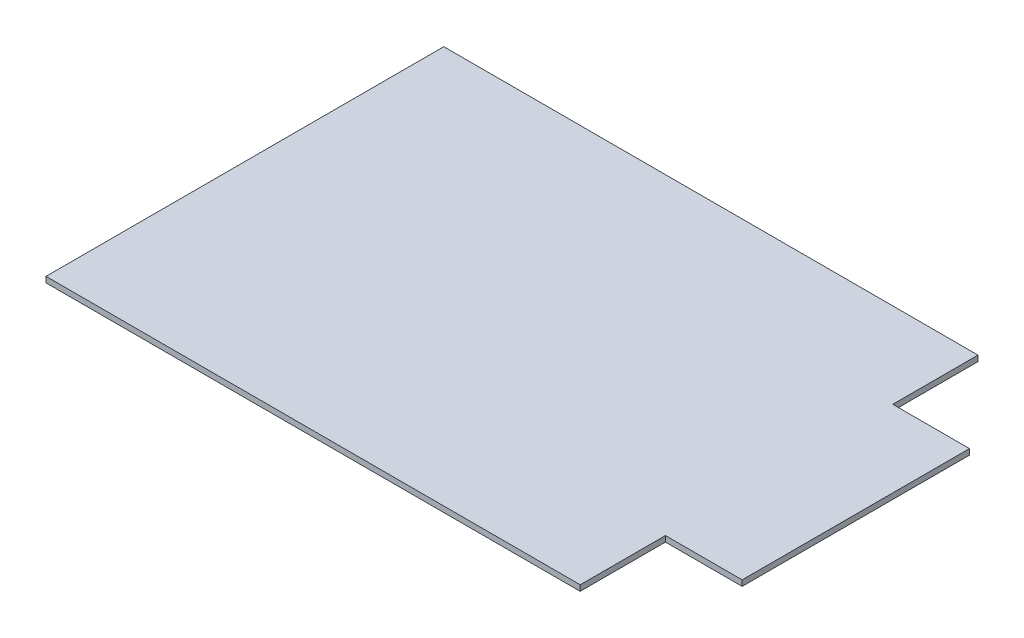
SolidWorks part; units mm, degrees
ref_plane "Front Plane" through (0, 0, 0) normal (0, 0, 1) x (1, 0, 0)
ref_plane "Top Plane" through (0, 0, 0) normal (0, 1, 0) x (1, 0, 0)
ref_plane "Right Plane" through (0, 0, 0) normal (1, 0, 0) x (0, 0, -1)
sketch "Sketch1" plane through (0, 0, 0) normal (0, 1, 0) x (1, 0, 0)
  line L0 (-55.2047, 60.4757) -> (-55.2047, -79.5243)
  line L1 (-55.2047, -79.5243) -> (132.7953, -79.5243)
  line L2 (132.7953, -79.5243) -> (132.7953, -49.5243)
  line L3 (132.7953, -49.5243) -> (159.7953, -49.5243)
  line L4 (159.7953, -49.5243) -> (159.7953, 30.4757)
  line L5 (159.7953, 30.4757) -> (132.7953, 30.4757)
  line L6 (132.7953, 30.4757) -> (132.7953, 60.4757)
  line L7 (132.7953, 60.4757) -> (-55.2047, 60.4757)
  dimension "D1" = 80
  dimension "D2" = 30
  dimension "D3" = 30
  dimension "D4" = 188
  dimension "D6" = 27
  dimension "D7" = 27
extrude "Boss-Extrude1" add sketch "Sketch1" along normal blind 2
